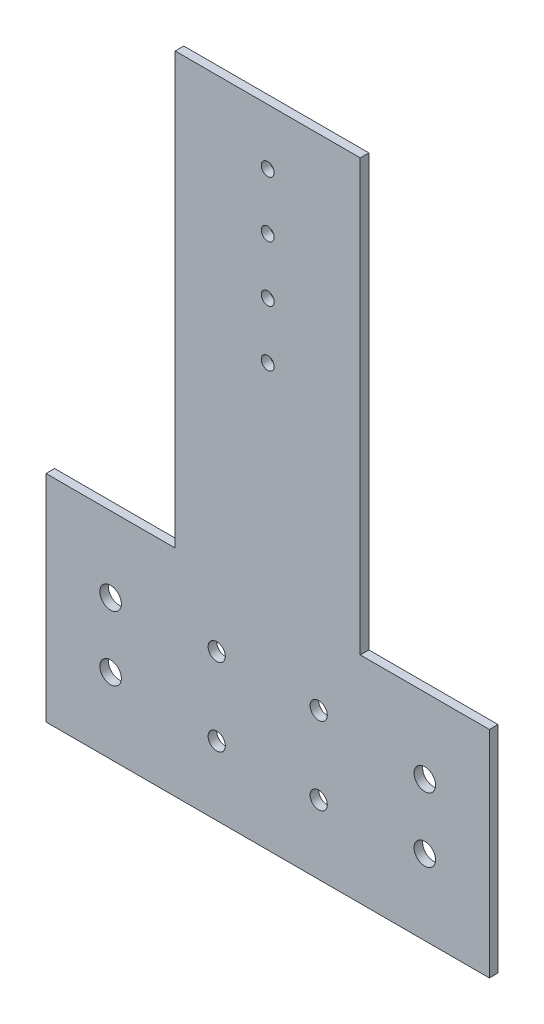
SolidWorks part; units mm, degrees
ref_plane "Front Plane" through (0, 0, 0) normal (0, 0, 1) x (1, 0, 0)
ref_plane "Top Plane" through (0, 0, 0) normal (0, 1, 0) x (1, 0, 0)
ref_plane "Right Plane" through (0, 0, 0) normal (1, 0, 0) x (0, 0, -1)
sketch "Sketch1" plane through (0, 0, 0) normal (0, 0, 1) x (1, 0, 0)
  line L1 (-51.5, -25) -> (51.5, -25)
  line L2 (-51.5, -25) -> (-51.5, 25)
  line L3 (-51.5, 25) -> (51.5, 25)
  line L4 (51.5, -25) -> (51.5, 25)
  line L5 (-51.5, -25) -> (51.5, 25) construction
  line L6 (-51.5, 25) -> (51.5, -25) construction
  point P0 (0, 0)
  dimension "D1" = 103
  dimension "D2" = 50
extrude "Boss-Extrude1" add sketch "Sketch1" along normal blind 2
sketch "Sketch2" plane through (0, 0, 2) normal (0, 0, 1) x (1, 0, 0)
  line L0 (0, 25) -> (0, -25) construction
  line L1 (51.5, 25) -> (-51.5, 25) construction
  line L2 (-51.5, -25) -> (51.5, -25) construction
  line L3 (-36.5, 25) -> (-36.5, -25) construction
  line L4 (36.5, 25) -> (36.5, -25) construction
  line L5 (-51.5, 25) -> (-51.5, -25) construction
  line L6 (51.5, -25) -> (51.5, 25) construction
  dimension "D1" = 15
  dimension "D2" = 15
sketch "Sketch3" plane through (0, 0, 2) normal (0, 0, 1) x (1, 0, 0)
  line L1 (-11.845, -9) -> (11.845, -9) construction
  line L2 (-11.845, -9) -> (-11.845, 9) construction
  line L3 (-11.845, 9) -> (11.845, 9) construction
  line L4 (11.845, -9) -> (11.845, 9) construction
  line L5 (-11.845, -9) -> (11.845, 9) construction
  line L6 (-11.845, 9) -> (11.845, -9) construction
  circle A0 centre (-11.845, 9) radius 2
  circle A1 centre (-11.845, -9) radius 2
  circle A2 centre (11.845, -9) radius 2
  circle A3 centre (11.845, 9) radius 2
  point P0 (0, 0)
  dimension "D3" = 4
  dimension "D4" = 4
  dimension "D5" = 4
  dimension "D6" = 4
  dimension "D1" = 23.69
  dimension "D2" = 18
extrude "Cut-Extrude1" cut sketch "Sketch3" against normal blind 7
sketch "Sketch4" plane through (0, 0, 2) normal (0, 0, 1) x (1, 0, 0)
  line L0 (-51.5, 0) -> (51.5, 0) construction
  line L1 (-51.5, 25) -> (-51.5, -25) construction
  line L2 (51.5, -25) -> (51.5, 25) construction
  line L3 (-36.5, 25) -> (-36.5, -25) construction
  line L4 (0, -55) -> (0, 55) construction
  circle A0 centre (-36.5, 7.5) radius 2.5
  circle A1 centre (-36.5, -7.5) radius 2.5
  circle A2 centre (36.5, -7.5) radius 2.5
  circle A3 centre (36.5, 7.5) radius 2.5
  dimension "D1" = 5
  dimension "D2" = 5
  dimension "D3" = 15
  dimension "D4" = 7.5
extrude "Cut-Extrude2" cut sketch "Sketch4" against normal blind 7
sketch "Sketch6" plane through (0, 25, 0) normal (0, 1, 0) x (1, 0, 0)
  line L0 (51.5, -2) -> (-51.5, -2) construction
  line L1 (-21.5, -2) -> (21.5, -2)
  line L2 (-21.5, -2) -> (-21.5, 0)
  line L3 (-21.5, 0) -> (21.5, 0)
  line L4 (21.5, -2) -> (21.5, 0)
  line L5 (51.5, 0) -> (-51.5, 0) construction
  line L6 (-51.5, -2) -> (-51.5, 0) construction
  line L7 (51.5, -2) -> (51.5, 0) construction
  dimension "D1" = 30
  dimension "D2" = 30
extrude "Boss-Extrude3" add sketch "Sketch6" along normal blind 100
chamfer "Chamfer1" [suppressed] distance 30 angle 52
sketch "Sketch7" plane through (0, 0, 2) normal (0, 0, 1) x (1, 0, 0)
  line L0 (0, 125) -> (0, 73) construction
  line L1 (-21.5, 125) -> (21.5, 125) construction
  circle A0 centre (0, 112) radius 1.5
  circle A1 centre (0, 99) radius 1.5
  circle A2 centre (0, 86) radius 1.5
  circle A3 centre (0, 73) radius 1.5
  dimension "D1" = 3
  dimension "D2" = 3
  dimension "D3" = 3
  dimension "D4" = 3
  dimension "D5" = 13
  dimension "D6" = 13
  dimension "D7" = 13
  dimension "D8" = 13
extrude "Cut-Extrude3" cut sketch "Sketch7" against normal blind 30
